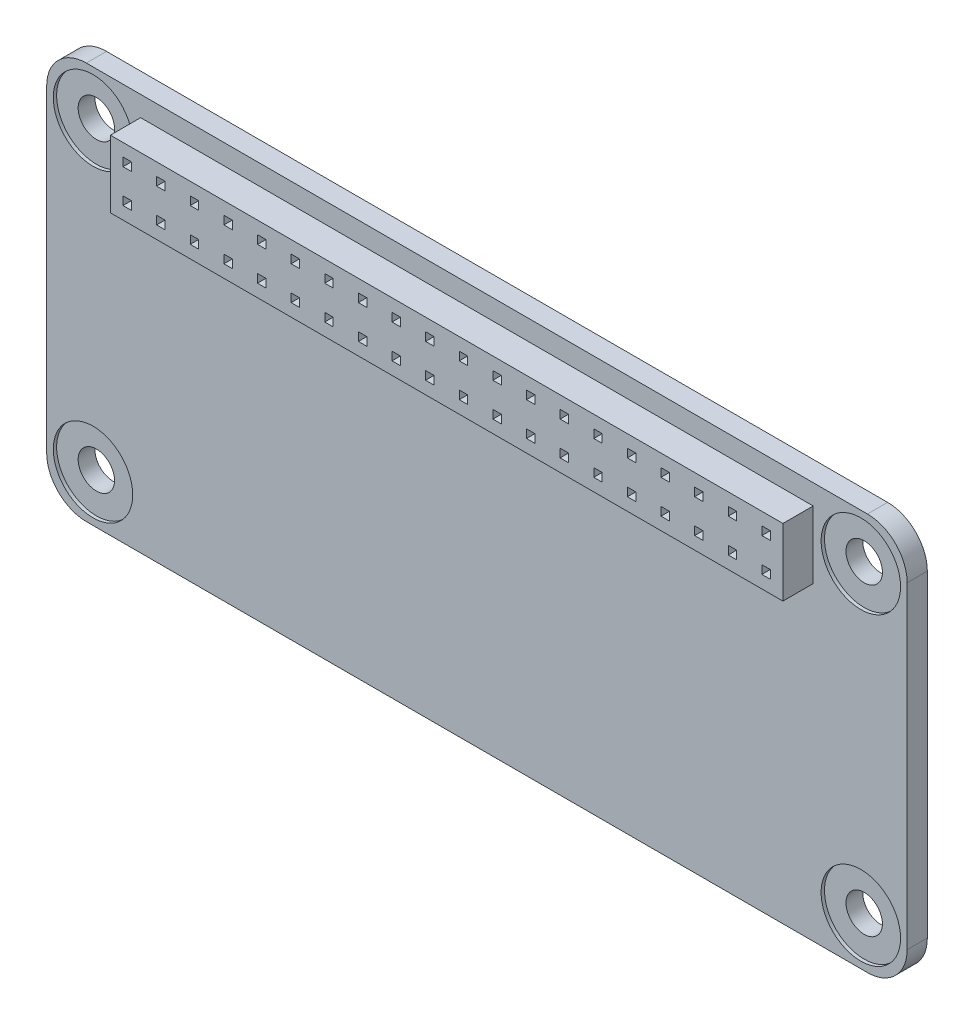
SolidWorks part; units mm, degrees
ref_plane "Front Plane" through (0, 0, 0) normal (0, 0, 1) x (1, 0, 0)
ref_plane "Top Plane" through (0, 0, 0) normal (0, 1, 0) x (1, 0, 0)
ref_plane "Right Plane" through (0, 0, 0) normal (1, 0, 0) x (0, 0, -1)
sketch "Sketch1" plane through (0, 0, 0) normal (0, 0, 1) x (1, 0, 0)
  line L1 (0, 0) -> (65, 0)
  line L2 (0, 0) -> (0, 30)
  line L3 (0, 30) -> (65, 30)
  line L4 (65, 0) -> (65, 30)
  dimension "D1" = 65
  dimension "D2" = 30
extrude "Boss-Extrude1" add sketch "Sketch1" along normal blind 1.524
fillet "Fillet1" radius 3 4 edges at (65, 30, 0.762) (65, 0, 0.762) (0, 0, 0.762) (0, 30, 0.762)
sketch "Sketch2" plane through (0, 0, 1.524) normal (0, 0, 1) x (1, 0, 0)
  line L0 (3.5, 3.5) -> (61.5, 3.5) construction
  line L1 (61.5, 3.5) -> (61.5, 26.5) construction
  line L2 (61.5, 26.5) -> (3.5, 26.5) construction
  line L3 (3.5, 26.5) -> (3.5, 3.5) construction
  line L4 (32.5, 26.5) -> (32.5, 30) construction
  line L5 (62, 30) -> (3, 30) construction
  line L6 (0, 15) -> (3.5, 15) construction
  line L7 (0, 27) -> (0, 3) construction
  circle A0 centre (3.5, 26.5) radius 1.375
  circle A1 centre (61.5, 26.5) radius 1.375
  circle A2 centre (61.5, 3.5) radius 1.375
  circle A3 centre (3.5, 3.5) radius 1.375
  dimension "D1" = 2.75
  dimension "D2" = 23
  dimension "D3" = 58
extrude "Cut-Extrude1" cut sketch "Sketch2" against normal through all
sketch "Sketch3" plane through (0, 0, 1.524) normal (0, 0, 1) x (1, 0, 0)
  circle A0 centre (3.5, 26.5) radius 3
  circle A1 centre (61.5, 26.5) radius 3
  circle A2 centre (61.5, 3.5) radius 3
  circle A3 centre (3.5, 3.5) radius 3
  dimension "D1" = 6
extrude "Cut-Extrude2" cut sketch "Sketch3" against normal blind 0.254
sketch "Sketch8" plane through (0, 0, 1.524) normal (0, 0, 1) x (1, 0, 0)
  line L0 (32.5, 23.396) -> (32.5, 28.476) construction
  line L1 (7.1, 28.476) -> (57.9, 28.476)
  line L2 (7.1, 28.476) -> (7.1, 23.396)
  line L3 (7.1, 23.396) -> (57.9, 23.396)
  line L4 (57.9, 28.476) -> (57.9, 23.396)
  line L5 (62, 30) -> (3, 30) construction
  circle A0 centre (3.5, 26.5) radius 1.375 construction
  dimension "D1" = 5.08
  dimension "D2" = 50.8
  dimension "D3" = 29
  dimension "D4" = 1.524
extrude "Boss-Extrude8" add sketch "Sketch8" along normal blind 2.286
sketch "Sketch9" plane through (0, 0, 3.81) normal (0, 0, 1) x (1, 0, 0)
  line L0 (7.1, 25.936) -> (57.9, 25.936) construction
  line L1 (8.0525, 27.5235) -> (8.6875, 27.5235)
  line L2 (8.0525, 27.5235) -> (8.0525, 26.8885)
  line L3 (8.0525, 26.8885) -> (8.6875, 26.8885)
  line L4 (8.6875, 27.5235) -> (8.6875, 26.8885)
  line L5 (8.0525, 24.9835) -> (8.6875, 24.9835)
  line L6 (8.0525, 24.9835) -> (8.0525, 24.3485)
  line L7 (8.0525, 24.3485) -> (8.6875, 24.3485)
  line L8 (8.6875, 24.9835) -> (8.6875, 24.3485)
  line L9 (7.1, 28.476) -> (7.1, 23.396) construction
  line L10 (57.9, 23.396) -> (57.9, 28.476) construction
  line L11 (8.37, 24.9835) -> (8.37, 25.936) construction
  line L12 (8.37, 25.936) -> (8.37, 26.8885) construction
  line L13 (8.0525, 27.206) -> (7.1, 27.206) construction
  line L14 (7.1, 28.476) -> (7.1, 23.396) construction
  line L15 (8.0525, 24.666) -> (7.1, 24.666) construction
  dimension "D1" = 0.635
  dimension "D2" = 0.635
  dimension "D3" = 2.54
  dimension "D4" = 1.27
extrude "Cut-Extrude3" cut sketch "Sketch9" against normal through all contours L7 L8 L5 L6 | L3 L4 L1 L2
pattern_linear "LPattern1" count 20 spacing 2.54 along (1, 0, 0) of "Cut-Extrude3"
